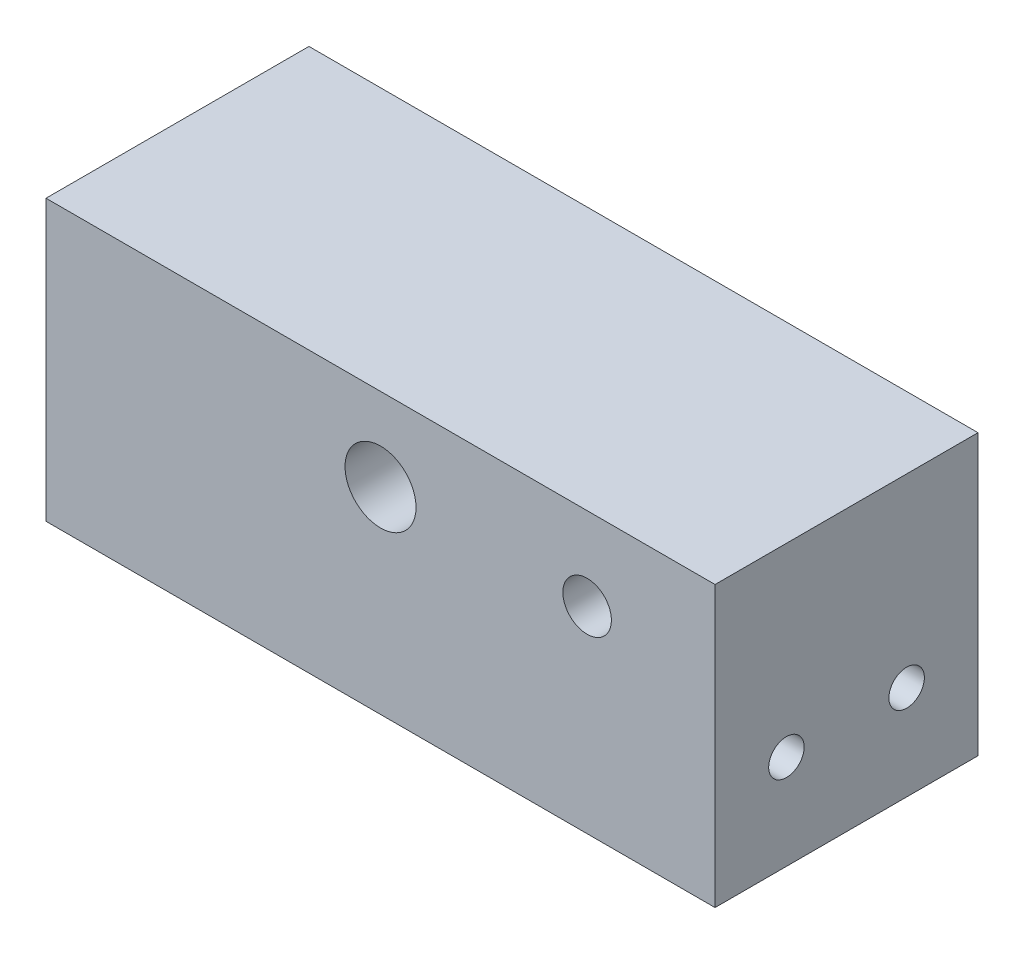
SolidWorks part; units mm, degrees
material "ABS"
ref_plane "X-Y Datum" through (0, 0, 0) normal (0, 0, 1) x (1, 0, 0)
ref_plane "X-Z Datum" through (0, 0, 0) normal (0, 1, 0) x (1, 0, 0)
ref_plane "Y-Z Datum" through (0, 0, 0) normal (1, 0, 0) x (0, 0, -1)
sketch "Sketch1" plane through (0, 0, 0) normal (0, 0, 1) x (1, 0, 0)
  line L1 (-28.275, 11.1125) -> (28.275, 11.1125)
  line L2 (-28.275, 11.1125) -> (-28.275, -11.1125)
  line L3 (-28.275, -11.1125) -> (28.275, -11.1125)
  line L4 (28.275, 11.1125) -> (28.275, -11.1125)
  line L5 (-28.275, 11.1125) -> (28.275, -11.1125) construction
  line L6 (-28.275, -11.1125) -> (28.275, 11.1125) construction
  point P0 (0, 0)
  dimension "D1" = 56.55
  dimension "D2" = 22.225
extrude "Boss-Extrude1" add sketch "Sketch1" along normal blind 22.225 contours L2 L3 L4 L1
sketch "Sketch2" plane through (0, 0, 22.225) normal (0, 0, 1) x (1, 0, 0)
  line L0 (-23.5453, 4.1125) -> (31.0951, 4.1125) construction
  line L1 (0, 11.1125) -> (0, -11.1125) construction
  line L2 (-28.275, 11.1125) -> (28.275, 11.1125) construction
  line L3 (-17.4625, 4.1125) -> (17.4625, 4.1125) construction
  line L4 (-28.275, -11.1125) -> (28.275, -11.1125) construction
  circle A0 centre (17.4625, 4.1125) radius 2.05
  circle A1 centre (-17.4625, 4.1125) radius 2.05 construction
  circle A2 centre (0, 4.1125) radius 3
  point P10 (0, 4.1125)
  dimension "D1" = 4.1
  dimension "D4" = 6
  dimension "D2" = 34.925
  dimension "D3" = 7
extrude "Cut-Extrude1" cut sketch "Sketch2" against normal blind 10 contours A1 L0 L3 | L0 A1 L3 | L0 L3 A0 | L3 L0 A0 | A2
sketch "Sketch3" plane through (-28.275, 0, 0) normal (-1, 0, 0) x (0, 0, 1)
  line L0 (0, -4.5375) -> (22.225, -4.5375) construction
  line L1 (0, 11.1125) -> (0, -11.1125) construction
  line L2 (22.225, 184.8875) -> (22.225, -15.7125) construction
  line L3 (16.1925, -4.5375) -> (6.0325, -4.5375) construction
  line L4 (11.1125, 11.1125) -> (11.1125, -11.1125) construction
  line L5 (22.225, 11.1125) -> (0, 11.1125) construction
  line L6 (22.225, -11.1125) -> (0, -11.1125) construction
  line L7 (-277.475, -12.5375) -> (22.225, -12.5375) construction
  circle A0 centre (16.1925, -4.5375) radius 1.5
  circle A1 centre (6.0325, -4.5375) radius 1.5
  point P10 (11.1125, -4.5375)
  dimension "D1" = 3
  dimension "D2" = 10.16
  dimension "D3" = 8
extrude "Cut-Extrude2" cut sketch "Sketch3" against normal blind 8
sketch "Sketch5" plane through (0, -11.1125, 0) normal (0, -1, 0) x (1, 0, 0)
  line L4 (-28.275, 0) -> (28.275, 0)
  line L5 (28.275, 0) -> (28.275, 22.225)
  line L6 (28.275, 22.225) -> (-28.275, 22.225)
  line L7 (-28.275, 22.225) -> (-28.275, 0)
  line L8 (-28.275, 0) -> (28.275, 0)
  line L9 (28.275, 0) -> (28.275, 22.225)
  line L10 (28.275, 22.225) -> (-28.275, 22.225)
  line L11 (-28.275, 22.225) -> (-28.275, 0)
  dimension "D1" = 0
extrude "Boss-Extrude2" add sketch "Sketch5" along normal blind 1.4249
mirror "Mirror2" about plane through (0, 0, 0) normal (1, 0, 0) of "Cut-Extrude2"
sketch "Sketch6" plane through (0, 0, 0) normal (0, 0, -1) x (-1, 0, 0)
  line L0 (-28.275, 1.1125) -> (28.275, 1.1125) construction
  line L1 (-28.275, 11.1125) -> (-28.275, -12.5374) construction
  line L2 (28.275, 11.1125) -> (28.275, -12.5374) construction
  line L3 (-10, 1.1125) -> (10, 1.1125) construction
  line L5 (28.275, 11.1125) -> (-28.275, 11.1125) construction
  circle A1 centre (-10, 1.1125) radius 3.025
  circle A2 centre (10, 1.1125) radius 3.025
  point P10 (0, 1.1125)
  point P12 (-12.4695, -4.5676)
  point P13 (0, 0)
  dimension "D1" = 6.05
  dimension "D2" = 10
  dimension "D3" = 20
extrude "Cut-Extrude3" cut sketch "Sketch6" against normal blind 10
